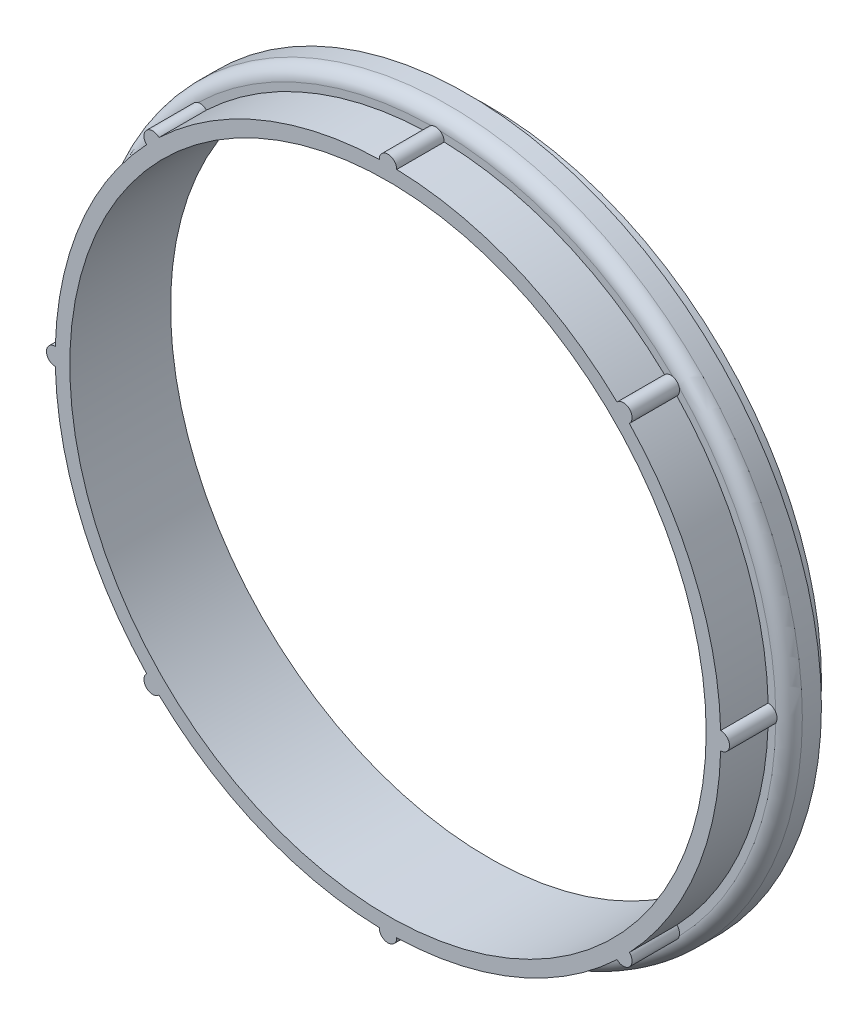
SolidWorks part; units mm, degrees
ref_plane "Front Plane" through (0, 0, 0) normal (0, 0, 1) x (1, 0, 0)
ref_plane "Top Plane" through (0, 0, 0) normal (0, 1, 0) x (1, 0, 0)
ref_plane "Right Plane" through (0, 0, 0) normal (1, 0, 0) x (0, 0, -1)
sketch "Sketch1" plane through (0, 0, 0) normal (0, 0, 1) x (1, 0, 0)
  circle A0 centre (0, 0) radius 47.8155
  circle A1 centre (0, 0) radius 53.975 construction
  circle A2 centre (0, 0) radius 45.72
  dimension "D1" = 107.95
  dimension "D2" = 2.0955
  dimension "D3" = 91.44
extrude "Boss-Extrude1" add sketch "Sketch1" along normal mid plane 14.478
sketch "Sketch2" plane through (0, 0, 0) normal (0, 0, 1) x (1, 0, 0)
  circle A0 centre (0, 0) radius 47.8155 construction
  circle A1 centre (0, 0) radius 47.8155
  circle A2 centre (0, 0) radius 53.975 construction
  circle A3 centre (0, 0) radius 53.975
extrude "Boss-Extrude2" add sketch "Sketch2" along normal mid plane 0.8255
sketch "Sketch3" plane through (0, 0, 7.239) normal (0, 0, 1) x (1, 0, 0)
  circle A0 centre (0, 47.8155) radius 1.2563
  circle A1 centre (0, 0) radius 47.8155 construction
  circle A2 centre (0, 0) radius 47.8155 construction
extrude "Boss-Extrude3" add sketch "Sketch3" against normal up to next
pattern_circular "CirPattern1" count 8 over 360 about axis through (0, 0, 0) along (0, 0, 1) of "Boss-Extrude3"
other "Move Face1" face at (53.975, 0, 0.4127) parameters "D1"=5.08
sketch "Sketch4" plane through (0, 0, 0) normal (1, 0, 0) x (0, 0, -1)
  line L0 (0, 0) -> (0, 50.8) construction
  line L1 (55.1926, 50.8) -> (-55.1926, 50.8) construction
  line L2 (-0.4128, 48.8907) -> (-0.4128, 35.0304) construction
  line L3 (0.4127, -48.895) -> (0.4127, 48.895) construction
  line L4 (-0.4128, 48.8907) -> (-0.4128, 35.0304) construction
  line L5 (0.4127, -48.895) -> (0.4127, 48.895) construction
  line L6 (0.4127, 48.8907) -> (0.4127, 35.0304) construction
  line L7 (-0.4128, 48.8907) -> (0.4127, 48.8907)
  line L8 (1.4966, 49.9745) -> (4.2402, 49.9745)
  line L9 (4.2402, 49.9745) -> (4.2402, 50.8)
  line L10 (4.2402, 50.8) -> (1.4966, 50.8)
  line L11 (29.7405, 0) -> (-30.5881, 0) construction
  arc A0 (-0.4128, 48.8907) -> (1.4966, 50.8) centre (1.4966, 48.8907) cw
  arc A1 (0.4127, 48.8907) -> (1.4966, 49.9745) centre (1.4966, 48.8907) cw
  arc A2 (0.4127, 48.8907) -> (1.4966, 49.9745) centre (1.4966, 48.8907) cw construction
  point P5 (0, 50.8)
  dimension "D1" = 50.8
  dimension "D2" = 0.8255
  dimension "D3" = 0.8255
revolve "Revolve2" add sketch "Sketch4" angle 360 about L11
